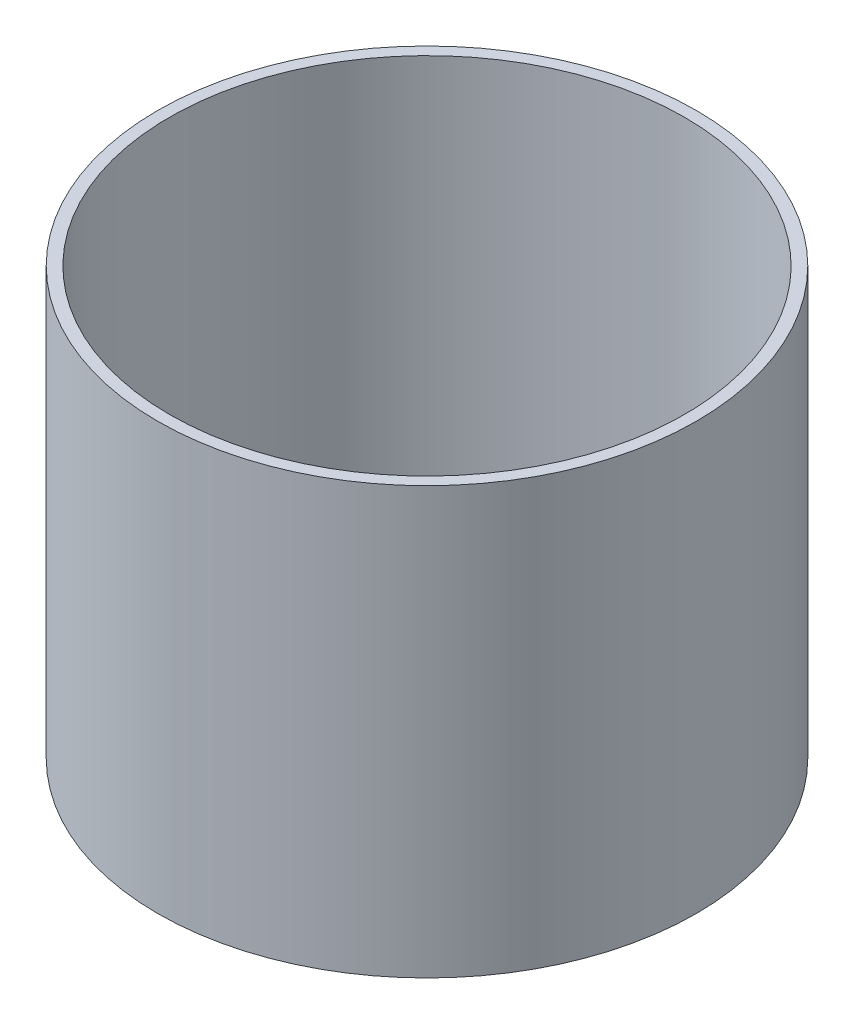
SolidWorks part; units mm, degrees
ref_plane "Front Plane" through (0, 0, 0) normal (0, 0, 1) x (1, 0, 0)
ref_plane "Top Plane" through (0, 0, 0) normal (0, 1, 0) x (1, 0, 0)
ref_plane "Right Plane" through (0, 0, 0) normal (1, 0, 0) x (0, 0, -1)
sketch "Sketch1" plane through (0, 0, 0) normal (0, 0, 1) x (1, 0, 0)
  line L0 (0, -167.3495) -> (0, 121.2323) construction
  line L1 (0, -85.4875) -> (109.3, -85.4875)
  line L2 (109.3, -85.4875) -> (109.3, 90.4875)
  line L3 (109.3, 90.4875) -> (114.3, 90.4875)
  line L4 (114.3, 90.4875) -> (114.3, -90.4875)
  line L5 (114.3, -90.4875) -> (0, -90.4875)
  line L6 (0, -90.4875) -> (0, -85.4875)
  point P5 (114.3, 0)
  dimension "D1" = 180.975
  dimension "D2" = 228.6
  dimension "D3" = 5
revolve "Revolve1" add sketch "Sketch1" angle 360 about L0
